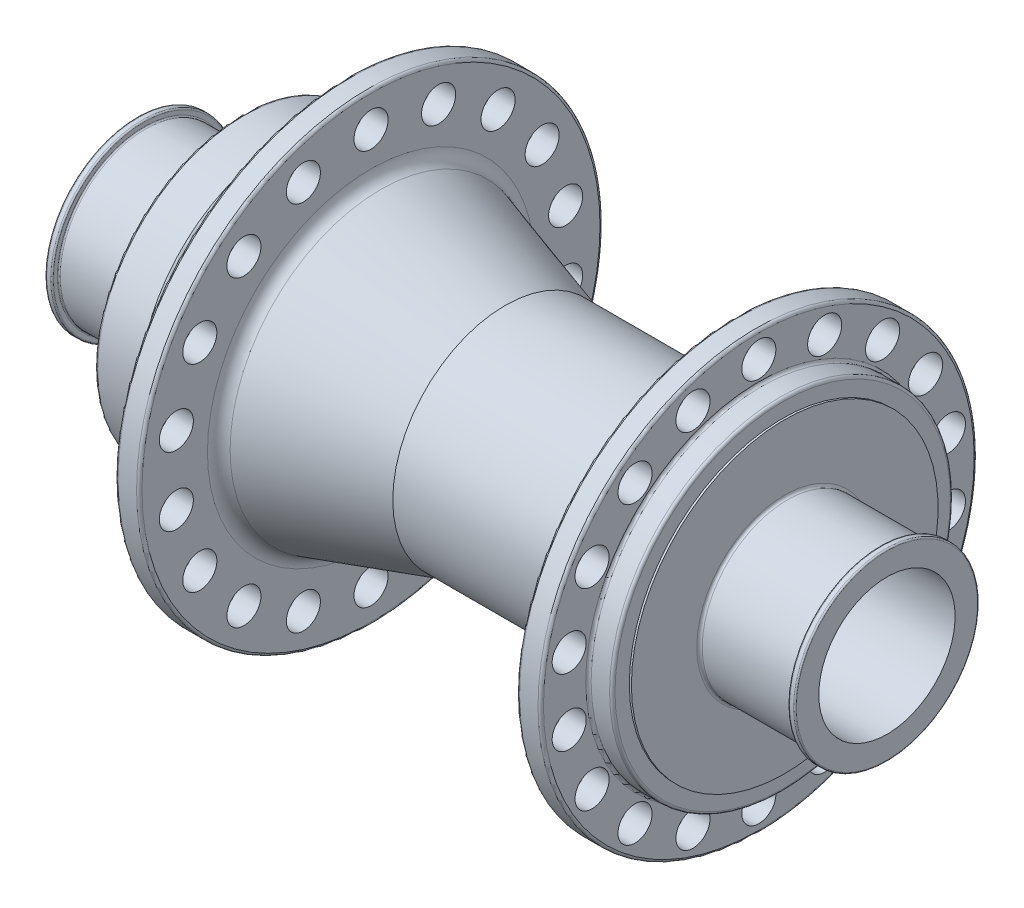
SolidWorks part; units mm, degrees
ref_plane "Płaszczyzna przednia" through (0, 0, 0) normal (0, 0, 1) x (1, 0, 0)
ref_plane "Płaszczyzna górna" through (0, 0, 0) normal (0, 1, 0) x (1, 0, 0)
ref_plane "Płaszczyzna prawa" through (0, 0, 0) normal (1, 0, 0) x (0, 0, -1)
sketch "Szkic1" plane through (0, 0, 0) normal (0, 0, 1) x (1, 0, 0)
  line L0 (0, 0) -> (110, 0)
  line L1 (0, 0) -> (0, 3.3)
  line L2 (0.2, 3.5) -> (0.8, 3.5)
  line L3 (1, 3.3) -> (1, 2.7)
  line L4 (1.2, 2.5) -> (14.6, 2.5)
  line L5 (15, 2.9) -> (15, 6.25)
  line L6 (15.2, 6.45) -> (15.3, 6.45)
  line L7 (15.3, 6.45) -> (15.3, 11.1)
  line L8 (15.7, 11.5) -> (21.7383, 11.5)
  line L9 (22.1247, 11.2035) -> (23.7206, 5.2476)
  line L10 (24.1069, 4.9511) -> (30.4, 4.9511)
  line L11 (30.8, 5.3511) -> (30.8, 23.6)
  line L12 (31.2, 24) -> (33.9, 24)
  line L13 (34.3, 23.6) -> (34.3, 14)
  line L14 (110, 0) -> (110, 3.3)
  line L15 (109.8, 3.5) -> (109.2, 3.5)
  line L16 (109, 3.3) -> (109, 2.7)
  line L17 (108.8, 2.5) -> (95.4, 2.5)
  line L18 (95, 2.9) -> (95, 12.5)
  line L19 (95, 12.5) -> (94.7, 12.5)
  line L20 (94.7, 12.5) -> (94.7, 14.6)
  line L21 (94.3, 15) -> (91.6, 15)
  line L22 (91.2, 15.4) -> (91.2, 21.6)
  line L23 (90.8, 22) -> (88.1, 22)
  line L24 (87.7, 21.6) -> (87.7, 10.5013)
  line L25 (53.9908, 6.5) -> (78.4942, 6.5)
  line L26 (78.4942, 6.5) -> (86.2176, 8.5695)
  line L27 (53.9908, 6.5) -> (35.7153, 12.0874)
  line L28 (0, -10) -> (110, -10) construction
  arc A0 (109, 2.7) -> (108.8, 2.5) centre (108.8, 2.7) cw
  arc A1 (110, 3.3) -> (109.8, 3.5) centre (109.8, 3.3) ccw
  arc A2 (109.2, 3.5) -> (109, 3.3) centre (109.2, 3.3) ccw
  arc A3 (15, 6.25) -> (15.2, 6.45) centre (15.2, 6.25) cw
  arc A4 (1, 2.7) -> (1.2, 2.5) centre (1.2, 2.7) ccw
  arc A5 (0.8, 3.5) -> (1, 3.3) centre (0.8, 3.3) cw
  arc A6 (0, 3.3) -> (0.2, 3.5) centre (0.2, 3.3) cw
  arc A7 (94.7, 14.6) -> (94.3, 15) centre (94.3, 14.6) ccw
  arc A8 (91.6, 15) -> (91.2, 15.4) centre (91.6, 15.4) cw
  arc A9 (95.4, 2.5) -> (95, 2.9) centre (95.4, 2.9) cw
  arc A10 (30.4, 4.9511) -> (30.8, 5.3511) centre (30.4, 5.3511) ccw
  arc A11 (23.7206, 5.2476) -> (24.1069, 4.9511) centre (24.1069, 5.3511) ccw
  arc A12 (21.7383, 11.5) -> (22.1247, 11.2035) centre (21.7383, 11.1) cw
  arc A13 (15.3, 11.1) -> (15.7, 11.5) centre (15.7, 11.1) cw
  arc A14 (14.6, 2.5) -> (15, 2.9) centre (14.6, 2.9) ccw
  arc A15 (91.2, 21.6) -> (90.8, 22) centre (90.8, 21.6) ccw
  arc A16 (88.1, 22) -> (87.7, 21.6) centre (88.1, 21.6) ccw
  arc A17 (33.9, 24) -> (34.3, 23.6) centre (33.9, 23.6) cw
  arc A18 (30.8, 23.6) -> (31.2, 24) centre (31.2, 23.6) cw
  arc A19 (34.3, 14) -> (35.7153, 12.0874) centre (36.3, 14) ccw
  arc A20 (87.7, 10.5013) -> (86.2176, 8.5695) centre (85.7, 10.5013) cw
  point P34 (110, 3.5)
  point P37 (109, 3.5)
  point P40 (15, 6.45)
  point P45 (1, 3.5)
  point P48 (0, 3.5)
  point P51 (94.7, 15)
  point P54 (91.2, 15)
  point P59 (30.8, 4.9511)
  point P62 (23.8, 4.9511)
  point P67 (15.3, 11.5)
  point P76 (34.3, 24)
  point P79 (30.8, 24)
  point P82 (34.3, 12.5201)
  dimension "D30" = 0.2
  dimension "D31" = 0.4
  dimension "D32" = 2
  dimension "D1" = 110
  dimension "D2" = 2.5
  dimension "D3" = 2.5
  dimension "D4" = 3.5
  dimension "D5" = 3.5
  dimension "D6" = 1
  dimension "D7" = 15.3
  dimension "D8" = 0.3
  dimension "D9" = 6.45
  dimension "D10" = 11.5
  dimension "D11" = 4.9511
  dimension "D12" = 3.5
  dimension "D13" = 24
  dimension "D14" = 14
  dimension "D15" = 0.3
  dimension "D16" = 15.5
  dimension "D17" = 12.5
  dimension "D18" = 15
  dimension "D19" = 22
  dimension "D20" = 15.3
  dimension "D21" = 1
  dimension "D22" = 53.4
  dimension "D23" = 3.5
  dimension "D24" = 6.5
  dimension "D25" = 17
  dimension "D26" = 15
  dimension "D27" = 24.5034
  dimension "D28" = 105
  dimension "D29" = 7
  dimension "D33" = 10
revolve "Obrót1" add sketch "Szkic1" angle 360 about L28
ref_plane "Płaszczyzna3" through (30.8, 0, 0) normal (-1, 0, 0) x (0, 0, 1)
sketch "Szkic5" plane through (30.8, 0, 0) normal (-1, 0, 0) x (0, 0, 1)
  circle A0 centre (0, -10) radius 29 construction
  circle A1 centre (0, 19) radius 2.5
  dimension "D1" = 58
  dimension "D2" = 5
extrude "Wytnij-wyciągnięcie1" cut sketch "Szkic5" against normal up to next
pattern_circular "Szyk kołowy1" count 18 over 360 about axis through (0, -10, 0) along (1, 0, 0) of "Wytnij-wyciągnięcie1"
ref_plane "Płaszczyzna4" through (91.2, 0, 0) normal (1, 0, 0) x (0, 0, -1)
sketch "Szkic6" plane through (91.2, 0, 0) normal (1, 0, 0) x (0, 0, -1)
  circle A0 centre (0, -10) radius 28.25 construction
  circle A1 centre (0, 18.25) radius 2.5
  dimension "D1" = 56.5
  dimension "D2" = 5
extrude "Wytnij-wyciągnięcie2" cut sketch "Szkic6" against normal up to next
pattern_circular "Szyk kołowy2" count 18 over 360 about axis through (0, -10, 0) along (1, 0, 0) of "Wytnij-wyciągnięcie2"
ref_plane "Płaszczyzna5" through (15.3, 0, 0) normal (-1, 0, 0) x (0, 0, 1)
sketch "Szkic7" plane through (15.3, 0, 0) normal (-1, 0, 0) x (0, 0, 1)
  circle A0 centre (0, -10) radius 18.75 construction
  circle A1 centre (0, 8.75) radius 1.5
  dimension "D1" = 3
extrude "Wytnij-wyciągnięcie3" cut sketch "Szkic7" against normal up to next
pattern_circular "Szyk kołowy3" count 6 over 360 about axis through (0, -10, 0) along (1, 0, 0) of "Wytnij-wyciągnięcie3"
